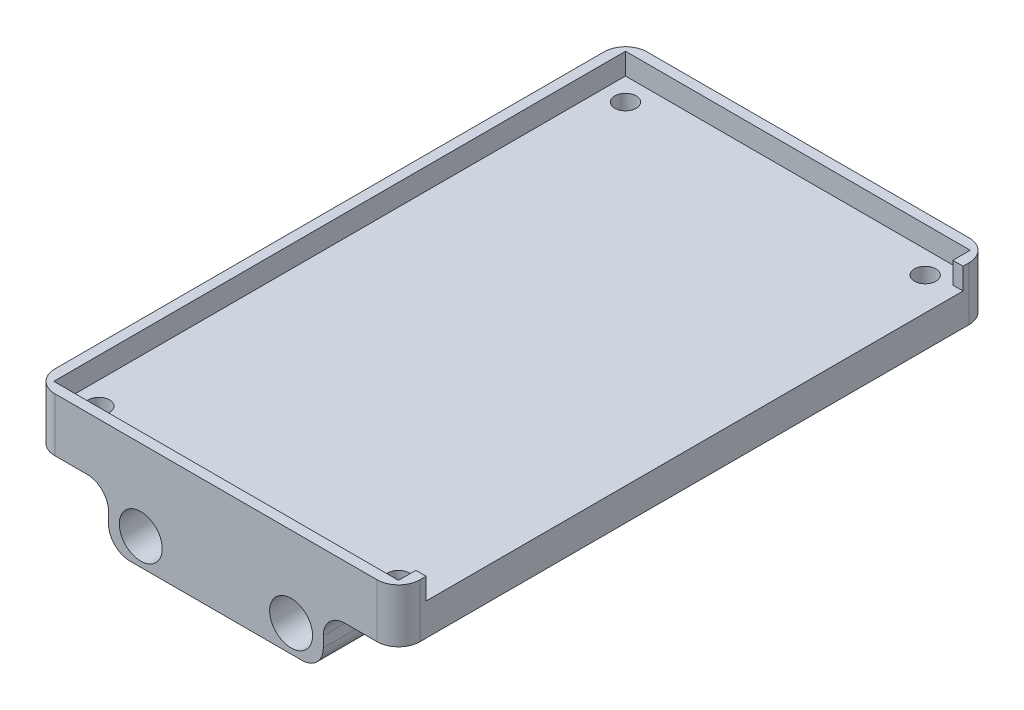
SolidWorks part; units mm, degrees
ref_plane "前视基准面" through (0, 0, 0) normal (0, 0, 1) x (1, 0, 0)
ref_plane "上视基准面" through (0, 0, 0) normal (0, 1, 0) x (1, 0, 0)
ref_plane "右视基准面" through (0, 0, 0) normal (1, 0, 0) x (0, 0, -1)
other "Configuration Table"
sketch "草图1" plane through (0, 0, 0) normal (0, 1, 0) x (1, 0, 0)
  line L1 (0, 0) -> (34, 0)
  line L2 (0, 0) -> (0, 55.14)
  line L3 (0, 55.14) -> (34, 55.14)
  line L4 (34, 0) -> (34, 55.14)
  dimension "D1" = 34
  dimension "D2" = 55.14
extrude "凸台-拉伸1" add sketch "草图1" along normal blind 5
sketch "草图2" plane through (0, 5, 0) normal (0, 1, 0) x (1, 0, 0)
  line L0 (0.95, 54.19) -> (33.05, 54.19)
  line L2 (0, 55.14) -> (0, 0)
  line L3 (0, 0) -> (34, 0)
  line L4 (34, 55.14) -> (34, 0)
  line L5 (33.05, 54.19) -> (33.05, 0.95)
  line L6 (0.95, 0.95) -> (33.05, 0.95)
  line L7 (0.95, 54.19) -> (0.95, 0.95)
  line L8 (0, 55.14) -> (34, 55.14) construction
  dimension "D1" = 0.95
extrude "切除-拉伸1" cut sketch "草图2" against normal blind 2 contours L0 L7 L6 L5
sketch "草图3" plane through (34, 0, 0) normal (1, 0, 0) x (0, 0, -1)
  line L0 (0, 5) -> (55.14, 5) construction
  line L1 (52.57, 10) -> (2.57, 10)
  line L2 (52.57, 10) -> (52.57, 0)
  line L3 (52.57, 0) -> (2.57, 0)
  line L4 (2.57, 10) -> (2.57, 0)
  line L5 (52.57, 10) -> (2.57, 0) construction
  line L6 (52.57, 0) -> (2.57, 10) construction
  line L7 (0, 0) -> (55.14, 0) construction
  point P0 (27.57, 5)
  dimension "D1" = 50
extrude "切除-拉伸2" cut sketch "草图3" against normal blind 2
fillet "圆角3" radius 2 1 edges at (0, 2.5, 0)
fillet "圆角4" radius 2 1 edges at (0, 2.5, -55.14)
fillet "圆角5" radius 2 1 edges at (34, 2.5, -55.14)
fillet "圆角6" radius 2 1 edges at (34, 2.5, 0)
sketch "草图5" plane through (0, 3, 0) normal (0, 1, 0) x (1, 0, 0)
  line L0 (17, -945.81) -> (17, 49054.19) construction
  line L1 (0.95, 54.19) -> (3.05, 54.19)
  line L2 (0.95, 54.19) -> (0.95, 52.09)
  line L3 (0.95, 52.09) -> (3.05, 52.09)
  line L4 (3.05, 54.19) -> (3.05, 52.09)
  line L6 (-999.05, 27.57) -> (49000.95, 27.57) construction
  line L7 (0.95, 54.19) -> (0.95, 0.95) construction
  line L8 (0.95, 54.19) -> (33.05, 54.19) construction
  circle A0 centre (3.05, 52.09) radius 1
  circle A1 centre (3.05, 3.05) radius 1
  circle A2 centre (30.95, 3.05) radius 1
  circle A3 centre (30.95, 52.09) radius 1
  point P13 (0.95, 27.57)
  point P16 (17, 54.19)
  dimension "D3" = 2
  dimension "D1" = 2.1
  dimension "D2" = 2.1
extrude "切除-拉伸3" cut sketch "草图5" against normal blind 5 contours A2 | A3 | A0 | A1
sketch "草图6" plane through (0, 3, 0) normal (0, 1, 0) x (1, 0, 0)
  line L0 (5.05, 49.09) -> (5.05, 6.05)
  line L1 (3.05, 52.09) -> (30.95, 52.09)
  line L2 (3.05, 52.09) -> (3.05, 3.05)
  line L3 (3.05, 3.05) -> (30.95, 3.05)
  line L4 (30.95, 52.09) -> (30.95, 3.05)
  line L5 (6.05, 5.05) -> (6.2547, 5.05)
  line L6 (28.95, 50.09) -> (28.95, 5.05)
  line L7 (6.05, 50.09) -> (6.2547, 50.09)
  line L8 (10.05, 49.09) -> (10.05, 6.05)
  line L13 (5.05, 50.09) -> (7.2547, 50.09)
  line L14 (5.05, 50.09) -> (5.05, 5.05)
  line L15 (5.05, 5.05) -> (7.2547, 5.05)
  line L16 (7.2547, 49.09) -> (7.2547, 6.05)
  line L17 (11.05, 50.09) -> (11.2547, 50.09)
  line L18 (12.2547, 49.09) -> (12.2547, 6.05)
  line L19 (11.05, 5.05) -> (11.2547, 5.05)
  line L20 (15.05, 49.09) -> (15.05, 6.05)
  line L21 (16.05, 50.09) -> (16.2547, 50.09)
  line L22 (17.2547, 49.09) -> (17.2547, 6.05)
  line L23 (16.05, 5.05) -> (16.2547, 5.05)
  line L24 (20.05, 49.09) -> (20.05, 6.05)
  line L25 (21.05, 50.09) -> (21.2547, 50.09)
  line L26 (22.2547, 49.09) -> (22.2547, 6.05)
  line L27 (21.05, 5.05) -> (21.2547, 5.05)
  line L28 (25.05, 49.09) -> (25.05, 6.05)
  line L29 (26.05, 50.09) -> (26.2547, 50.09)
  line L30 (27.2547, 49.09) -> (27.2547, 6.05)
  line L31 (26.05, 5.05) -> (26.2547, 5.05)
  line L32 (5.05, 50.09) -> (28.95, 50.09) construction
  line L33 (5.05, 5.05) -> (28.95, 5.05) construction
  line L34 (5.05, 50.09) -> (5.05, 5.05) construction
  arc A0 (6.2547, 50.09) -> (7.2547, 49.09) centre (6.2547, 49.09) cw
  arc A1 (6.2547, 5.05) -> (7.2547, 6.05) centre (6.2547, 6.05) ccw
  arc A2 (6.05, 5.05) -> (5.05, 6.05) centre (6.05, 6.05) cw
  arc A3 (5.05, 49.09) -> (6.05, 50.09) centre (6.05, 49.09) cw
  arc A4 (26.2547, 50.09) -> (27.2547, 49.09) centre (26.2547, 49.09) cw
  arc A5 (25.05, 49.09) -> (26.05, 50.09) centre (26.05, 49.09) cw
  arc A6 (26.2547, 5.05) -> (27.2547, 6.05) centre (26.2547, 6.05) ccw
  arc A7 (26.05, 5.05) -> (25.05, 6.05) centre (26.05, 6.05) cw
  arc A8 (21.2547, 5.05) -> (22.2547, 6.05) centre (21.2547, 6.05) ccw
  arc A9 (20.05, 6.05) -> (21.05, 5.05) centre (21.05, 6.05) ccw
  arc A10 (21.2547, 50.09) -> (22.2547, 49.09) centre (21.2547, 49.09) cw
  arc A11 (20.05, 49.09) -> (21.05, 50.09) centre (21.05, 49.09) cw
  arc A12 (16.2547, 50.09) -> (17.2547, 49.09) centre (16.2547, 49.09) cw
  arc A13 (15.05, 49.09) -> (16.05, 50.09) centre (16.05, 49.09) cw
  arc A14 (16.2547, 5.05) -> (17.2547, 6.05) centre (16.2547, 6.05) ccw
  arc A15 (16.05, 5.05) -> (15.05, 6.05) centre (16.05, 6.05) cw
  arc A16 (11.2547, 5.05) -> (12.2547, 6.05) centre (11.2547, 6.05) ccw
  arc A17 (10.05, 6.05) -> (11.05, 5.05) centre (11.05, 6.05) ccw
  arc A18 (11.2547, 50.09) -> (12.2547, 49.09) centre (11.2547, 49.09) cw
  arc A19 (10.05, 49.09) -> (11.05, 50.09) centre (11.05, 49.09) cw
  dimension "D3" = 1
  dimension "D4" = 1
  dimension "D1" = 2
  dimension "D2" = 5
extrude "切除-拉伸5" cut sketch "草图6" against normal blind 5 contours A3 L0 A2 L5 A1 L16 A0 L7 | A19 L8 A17 L19 A16 L18 A18 L17 | A11 L24 A9 L27 A8 L26 A10 L25 | A7 L31 A6 L30 A4 L29 A5 L28 | L20 A15 L23 A14 L22 A12 L21 A13
sketch "草图7" plane through (0, 0, 0) normal (0, -1, 0) x (1, 0, 0)
  line L1 (3.3369, -4.5252) -> (27.9146, -4.5252)
  line L2 (3.3369, -4.5252) -> (3.3369, -50.6148)
  line L3 (3.3369, -50.6148) -> (27.9146, -50.6148)
  line L4 (27.9146, -4.5252) -> (27.9146, -50.6148)
extrude "凸台-拉伸3" add sketch "草图7" against normal blind 3
sketch "草图8" plane through (0, 0, 0) normal (0, -1, 0) x (1, 0, 0)
  line L0 (17, 0) -> (17, -3)
  line L1 (2, 0) -> (32, 0) construction
  line L3 (7, -6) -> (27, -6)
  line L4 (7, -6) -> (7, 0)
  line L5 (7, 0) -> (27, 0)
  line L6 (27, -6) -> (27, 0)
  line L7 (7, -6) -> (27, 0) construction
  line L8 (7, 0) -> (27, -6) construction
  dimension "D1" = 3
  dimension "D2" = 6
  dimension "D3" = 20
extrude "凸台-拉伸5" add sketch "草图8" along normal blind 5
sketch "草图9" plane through (0, 0, 0) normal (0, -1, 0) x (1, 0, 0)
  line L0 (17, -55.14) -> (17, -52.14)
  line L1 (32, -55.14) -> (2, -55.14) construction
  line L3 (7, -55.14) -> (27, -55.14)
  line L4 (7, -55.14) -> (7, -49.14)
  line L5 (7, -49.14) -> (27, -49.14)
  line L6 (27, -55.14) -> (27, -49.14)
  line L7 (7, -55.14) -> (27, -49.14) construction
  line L8 (7, -49.14) -> (27, -55.14) construction
  dimension "D1" = 3
  dimension "D2" = 6
  dimension "D3" = 20
extrude "凸台-拉伸6" add sketch "草图9" along normal blind 5
sketch "草图10" plane through (0, 0, -55.14) normal (0, 0, -1) x (-1, 0, 0)
  line L1 (-27, -5) -> (-24, -5)
  line L2 (-27, -5) -> (-27, -2.5)
  line L3 (-27, -2.5) -> (-24, -2.5)
  line L4 (-24, -5) -> (-24, -2.5)
  line L5 (-7, -5) -> (-10, -5)
  line L6 (-7, -5) -> (-7, -2.5)
  line L7 (-7, -2.5) -> (-10, -2.5)
  line L8 (-10, -5) -> (-10, -2.5)
  circle A0 centre (-24, -2.5) radius 2
  circle A1 centre (-10, -2.5) radius 2
  dimension "D3" = 4
  dimension "D6" = 4
  dimension "D1" = 2.5
  dimension "D2" = 3
  dimension "D4" = 2.5
  dimension "D5" = 3
extrude "切除-拉伸6" cut sketch "草图10" against normal through all contours L7 A1 L8 | L8 A1 L7 | L3 A0 L4 | L4 A0 L3
fillet "圆角7" radius 2 1 edges at (7, -5, -52.14)
fillet "圆角8" radius 2 1 edges at (7, 0, -52.14)
fillet "圆角9" radius 2 1 edges at (27, -5, -52.14)
fillet "圆角10" radius 2 1 edges at (27, 0, -52.14)
fillet "圆角11" radius 2 1 edges at (7, -5, -3)
fillet "圆角12" radius 2 1 edges at (7, 0, -3)
fillet "圆角13" radius 2 1 edges at (27, -5, -3)
fillet "圆角14" radius 2 1 edges at (27, 0, -3)
sketch "草图11" plane through (0, 0, 0) normal (0, -1, 0) x (1, 0, 0)
  line L1 (32, -2.57) -> (34, -2.57)
  line L2 (32, -2.57) -> (32, -52.57)
  line L3 (32, -52.57) -> (34, -52.57)
  line L4 (34, -2.57) -> (34, -52.57)
extrude "凸台-拉伸7" add sketch "草图11" against normal blind 3
